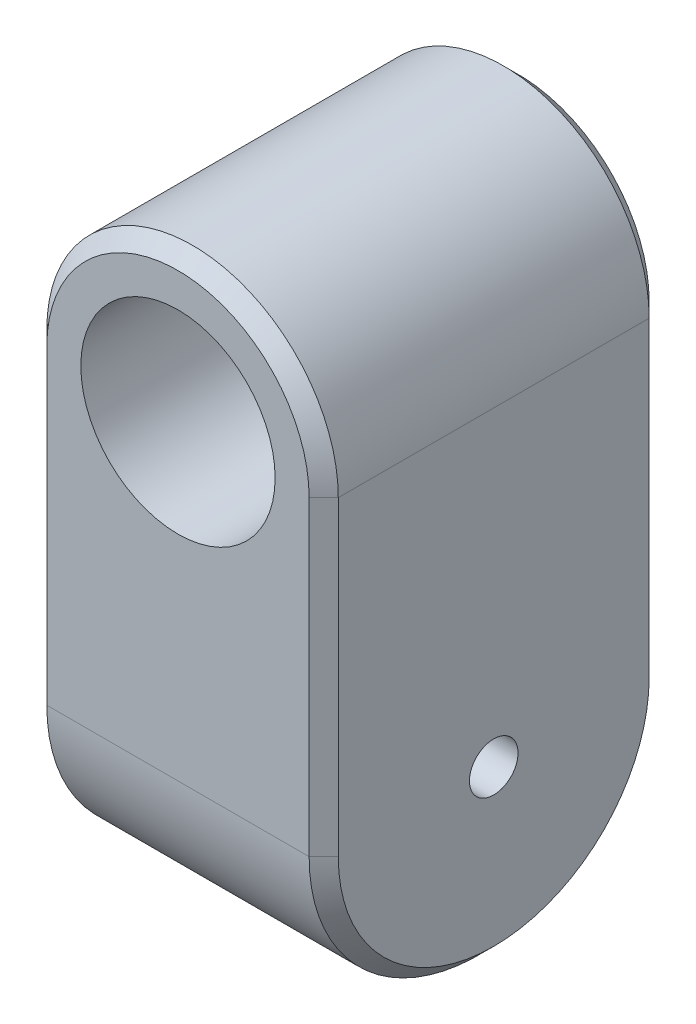
SolidWorks part; units mm, degrees
ref_plane "Front Plane" through (0, 0, 0) normal (0, 0, 1) x (1, 0, 0)
ref_plane "Top Plane" through (0, 0, 0) normal (0, 1, 0) x (1, 0, 0)
ref_plane "Right Plane" through (0, 0, 0) normal (1, 0, 0) x (0, 0, -1)
sketch "Sketch1" plane through (0, 0, 0) normal (1, 0, 0) x (0, 0, -1)
  line L1 (-87.5, 0) -> (87.5, 0) construction
  line L2 (-87.5, 0) -> (-87.5, 110)
  line L3 (-87.5, 110) -> (87.5, 110)
  line L4 (87.5, 0) -> (87.5, 110)
  arc A0 (-87.5, 0) -> (87.5, 0) centre (0, 0) ccw
  arc A1 (87.5, 0) -> (-87.5, 0) centre (0, 0) ccw construction
  circle A2 centre (0, 0) radius 12.5
  dimension "D1" = 87.5
  dimension "D3" = 25
  dimension "D2" = 110
extrude "Boss-Extrude1" add sketch "Sketch1" along normal mid plane 150
sketch "Sketch2" plane through (0, 0, 0) normal (0, 0, 1) x (1, 0, 0)
  line L0 (0, 0) -> (0, 160) construction
  line L1 (75, 110) -> (-75, 110) construction
  line L2 (75, 110) -> (75, 0) construction
  line L3 (-75, 160) -> (-75, 85)
  line L4 (-75, 110) -> (-75, 0) construction
  line L5 (-75, 85) -> (75, 85)
  line L6 (75, 85) -> (75, 160)
  circle A0 centre (0, 160) radius 50
  arc A1 (75, 160) -> (-75, 160) centre (0, 160) ccw
  arc A2 (0, 85) -> (75, 160) centre (0, 160) ccw construction
  arc A3 (-75, 160) -> (0, 85) centre (0, 160) ccw construction
  dimension "D1" = 100
extrude "Boss-Extrude2" add sketch "Sketch2" along normal up to surface and the other way up to surface up to face at (0, 55, 87.5) other way up to face at (0, 55, -87.5)
chamfer "Chamfer1" distance 7.5 angle 45 8 edges at (0, 235, 87.5) (0, 235, -87.5) (-75, 80, -87.5) (75, 80, -87.5) (-75, -87.5, 0) (75, -87.5, 0) (-75, 80, 87.5) (75, 80, 87.5)
